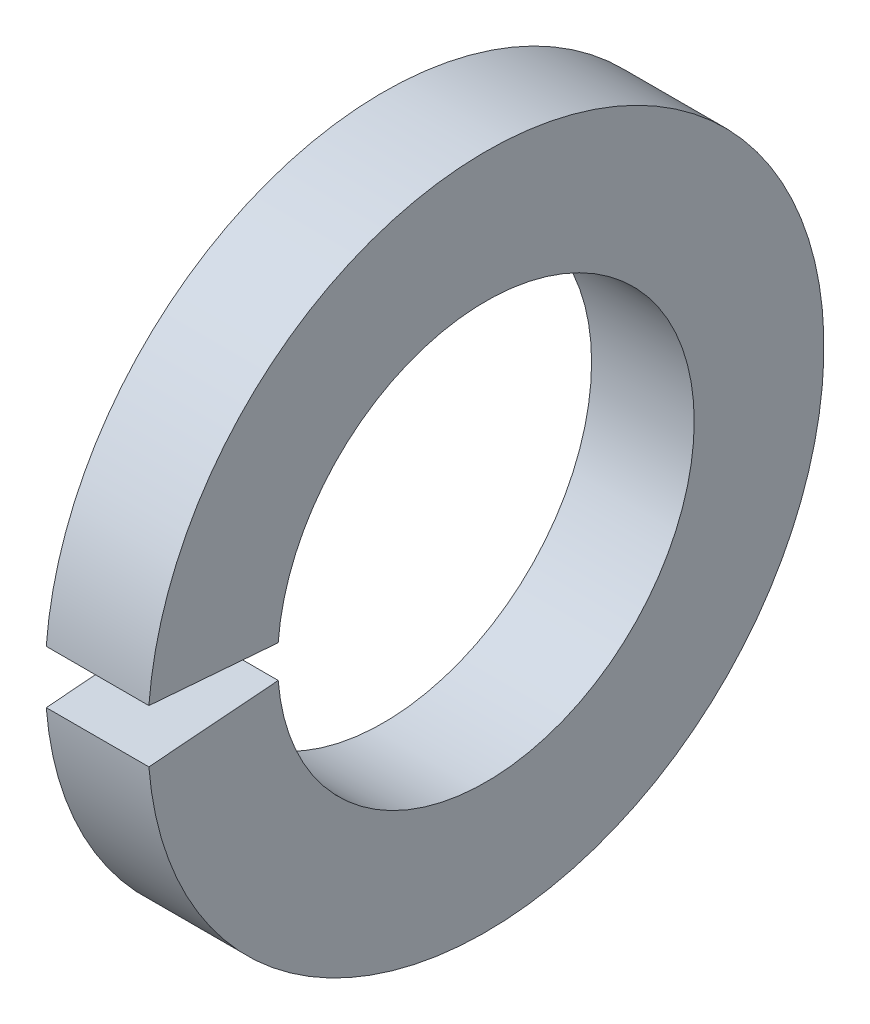
SolidWorks part; units mm, degrees
ref_plane "Plane1" through (0, 0, 0) normal (0, 0, 1) x (1, 0, 0)
ref_plane "Plane2" through (0, 0, 0) normal (0, 1, 0) x (1, 0, 0)
ref_plane "Plane3" through (0, 0, 0) normal (1, 0, 0) x (0, 0, -1)
sketch "Sketch1" plane through (0, 0, 0) normal (0, 0, 1) x (1, 0, 0)
  line L0 (-34.925, 0) -> (9.525, 0) construction
  line L1 (0, 12.8905) -> (0, 20.9169)
  line L2 (0, 20.9169) -> (-6.35, 20.9169)
  line L3 (-6.35, 20.9169) -> (-6.35, 12.8905)
  line L4 (-6.35, 12.8905) -> (0, 12.8905)
  dimension "Thickness" = 6.35
  dimension "Inside_dia" = 25.781
  dimension "Outside_dia" = 41.8338
revolve "Base-Revolve" add sketch "Sketch1" angle 360 about L0
sketch "Sketch2" plane through (0, 0, 0) normal (-1, 0, 0) x (0, -1, 0)
  line L0 (0, 0) -> (1.6739, 21.2695)
  line L1 (0, -3.175) -> (0, 12.7) construction
  line L2 (0, 0) -> (-1.6739, 21.2695)
  arc A0 (1.6739, 21.2695) -> (-1.6739, 21.2695) centre (0, 0) ccw
  dimension "Gap_ang" = 9
  dimension "D1" = 21.3352
extrude "Gap" cut sketch "Sketch2" along normal through all
equation "\"D1@Sketch2\" = \"Outside_dia@Sketch1\" * 0.51"
